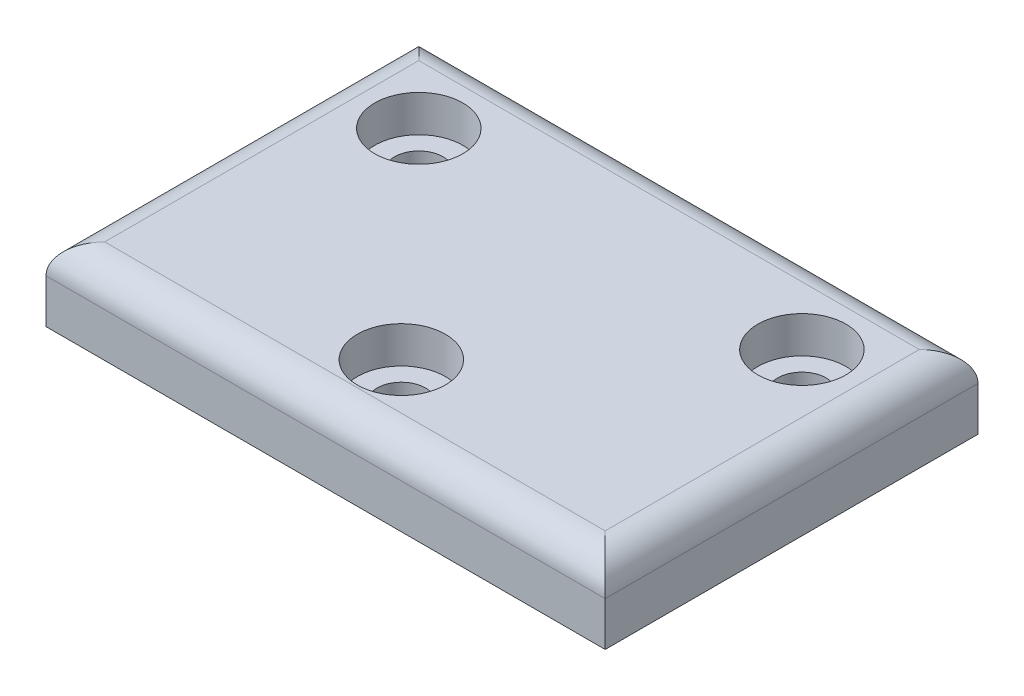
SolidWorks part; units mm, degrees
ref_plane "Front Plane" through (0, 0, 0) normal (0, 0, 1) x (1, 0, 0)
ref_plane "Top Plane" through (0, 0, 0) normal (0, 1, 0) x (1, 0, 0)
ref_plane "Right Plane" through (0, 0, 0) normal (1, 0, 0) x (0, 0, -1)
sketch "Sketch1" plane through (0, 0, 0) normal (0, 1, 0) x (1, 0, 0)
  line L0 (19.05, 25.4) -> (19.05, 0) construction
  line L1 (0, 25.4) -> (38.1, 25.4)
  line L2 (0, 25.4) -> (0, 0)
  line L3 (0, 0) -> (38.1, 0)
  line L4 (38.1, 25.4) -> (38.1, 0)
  circle A0 centre (19.05, 5.16) radius 1.65
  circle A1 centre (6, 19.4) radius 1.65
  circle A2 centre (32.1, 19.4) radius 1.65
  dimension "D6" = 3.3
  dimension "D1" = 25.4
  dimension "D2" = 38.1
  dimension "D3" = 5.16
  dimension "D4" = 6
  dimension "D5" = 6
extrude "Boss-Extrude1" add sketch "Sketch1" along normal blind 5
sketch "Sketch2" plane through (0, 5, 0) normal (0, 1, 0) x (1, 0, 0)
  circle A0 centre (6, 19.4) radius 3
  circle A2 centre (19.05, 5.16) radius 3
  circle A3 centre (32.1, 19.4) radius 3
  dimension "D1" = 6
extrude "Cut-Extrude1" cut sketch "Sketch2" against normal blind 2.5
fillet "Fillet1" radius 2 4 edges at (38.1, 5, -12.7) (19.05, 5, 0) (0, 5, -12.7) (19.05, 5, -25.4)
equation "\"Ø Smaller Shaft\"=6.35"
equation "\"Shaft Distance\"= 25.4"
equation "\"Width\"= \"Ø Smaller Shaft\" * 2 + \"Shaft Distance\" + \"Width End\" * 2"
equation "\"Width End\"= 6.35"
equation "\"Length\"= 38.1"
equation "\"Rod to Belt\"= 31.75 + 3"
equation "\"Nom Tolerance\"= 0.15"
equation "\"Belt\"= 6"
equation "\"Belt Thickness\"=1.38"
equation "\"Ø Pulley\"= 10.9"
equation "\"Pully Distance\"= 35"
equation "\"Ø Outer Washer\"= 12.7"
equation "\"Washer Thickness\"=2"
equation "\"M3 Screw Size\"= 3"
equation "\"D1@Sketch1\"=\"Width\"/2"
equation "\"D2@Sketch1\"=\"Length\""
equation "\"D6@Sketch1\"=\"M3 Screw Size\" + \"Nom Tolerance\"*2"
